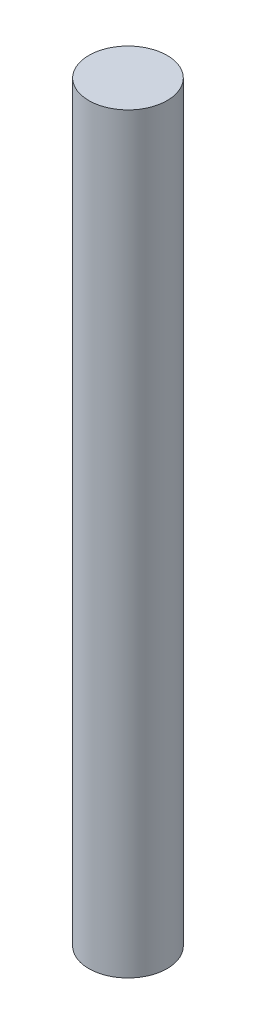
SolidWorks part; units mm, degrees
ref_plane "Front Plane" through (0, 0, 0) normal (0, 0, 1) x (1, 0, 0)
ref_plane "Top Plane" through (0, 0, 0) normal (0, 1, 0) x (1, 0, 0)
ref_plane "Right Plane" through (0, 0, 0) normal (1, 0, 0) x (0, 0, -1)
sketch "Sketch1" plane through (0, 0, 0) normal (0, 1, 0) x (1, 0, 0)
  circle A0 centre (0, 0) radius 0.625
  dimension "D1" = 1.25
extrude "Boss-Extrude1" add sketch "Sketch1" along normal blind 12
